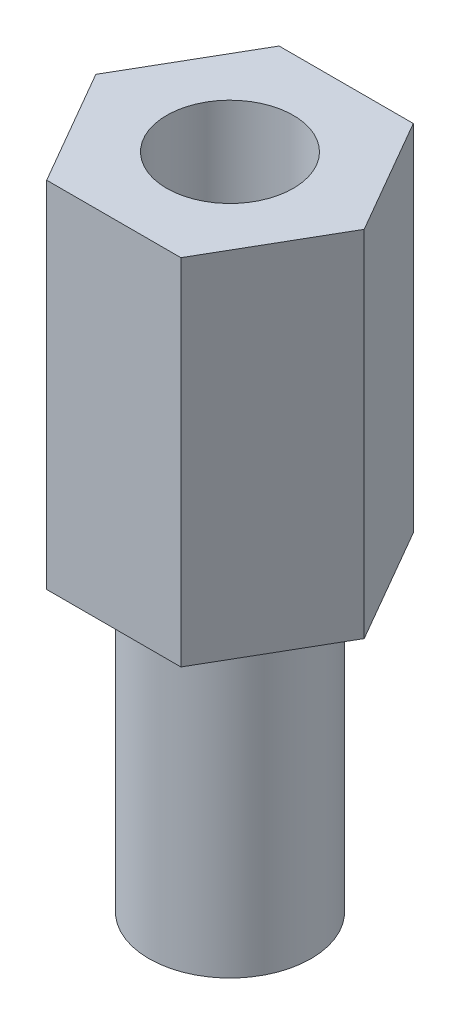
SolidWorks part; units mm, degrees
ref_plane "前视基准面" through (0, 0, 0) normal (0, 0, 1) x (1, 0, 0)
ref_plane "上视基准面" through (0, 0, 0) normal (0, 1, 0) x (1, 0, 0)
ref_plane "右视基准面" through (0, 0, 0) normal (1, 0, 0) x (0, 0, -1)
sketch "草图4" plane through (0, 0, 0) normal (0, 1, 0) x (1, 0, 0)
  line L0 (-12.7945, 0) -> (16.3015, 0) construction
  line L2 (1.325, -2.295) -> (2.65, 0)
  line L3 (2.65, 0) -> (1.325, 2.295)
  line L4 (1.325, 2.295) -> (-1.325, 2.295)
  line L5 (-1.325, 2.295) -> (-2.65, 0)
  line L6 (-2.65, 0) -> (-1.325, -2.295)
  line L7 (-1.325, -2.295) -> (1.325, -2.295)
  circle A0 centre (0, 0) radius 2.295 construction
  dimension "D1" = 5.3
extrude "凸台-拉伸1" add sketch "草图4" along normal blind 7
sketch "草图6" plane through (0, 0, 0) normal (0, -1, 0) x (-1, 0, 0)
  circle A0 centre (0, 0) radius 1.6
  dimension "D1" = 3.2
extrude "凸台-拉伸2" add sketch "草图6" along normal blind 6
cosmetic thread "装饰螺纹线1" parameters "D2"=2.5
sketch "草图7" plane through (0, 7, 0) normal (0, 1, 0) x (1, 0, 0)
  circle A0 centre (0, 0) radius 1.25
  dimension "D1" = 2.5
extrude "切除-拉伸1" cut sketch "草图7" against normal blind 5
cosmetic thread "装饰螺纹线2" parameters "D2"=3
